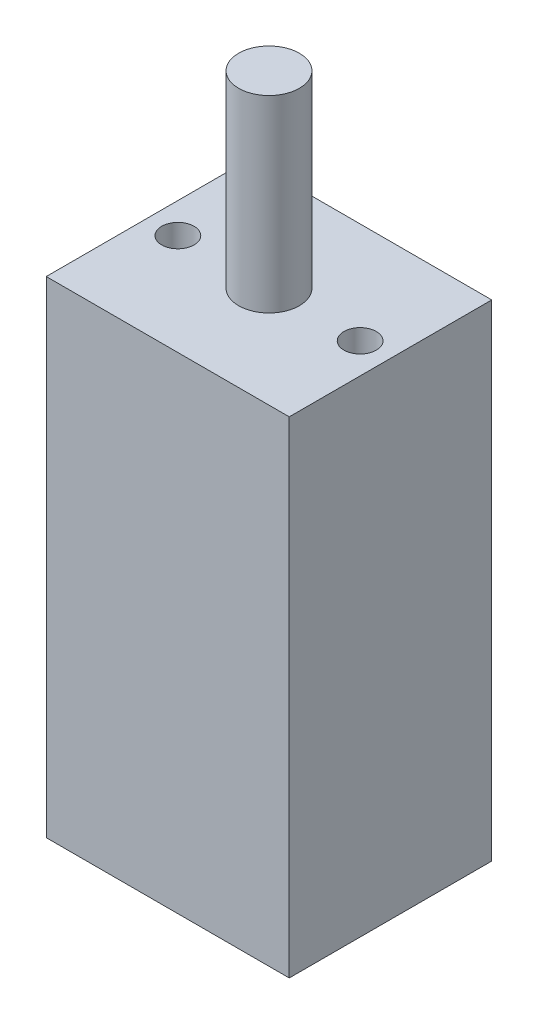
SolidWorks part; units mm, degrees
ref_plane "Front Plane" through (0, 0, 0) normal (0, 0, 1) x (1, 0, 0)
ref_plane "Top Plane" through (0, 0, 0) normal (0, 1, 0) x (1, 0, 0)
ref_plane "Right Plane" through (0, 0, 0) normal (1, 0, 0) x (0, 0, -1)
sketch "스케치1" plane through (0, 0, 0) normal (0, 1, 0) x (1, 0, 0)
  line L0 (-4.5, 0) -> (4.5, 0) construction
  line L1 (-6, -5) -> (6, -5)
  line L2 (-6, -5) -> (-6, 5)
  line L3 (-6, 5) -> (6, 5)
  line L4 (6, -5) -> (6, 5)
  line L5 (-6, -5) -> (6, 5) construction
  line L6 (-6, 5) -> (6, -5) construction
  circle A0 centre (4.5, 0) radius 0.8
  circle A1 centre (-4.5, 0) radius 0.8
  point P0 (0, 0)
  dimension "D3" = 1.6
  dimension "D4" = 1.6
  dimension "D1" = 10
  dimension "D2" = 12
  dimension "D5" = 9
extrude "보스-돌출1" add sketch "스케치1" along normal blind 24
sketch "스케치2" plane through (0, 24, 0) normal (0, 1, 0) x (1, 0, 0)
  circle A0 centre (0, 0) radius 1.5
  dimension "D1" = 3
extrude "보스-돌출2" add sketch "스케치2" along normal blind 9.3
